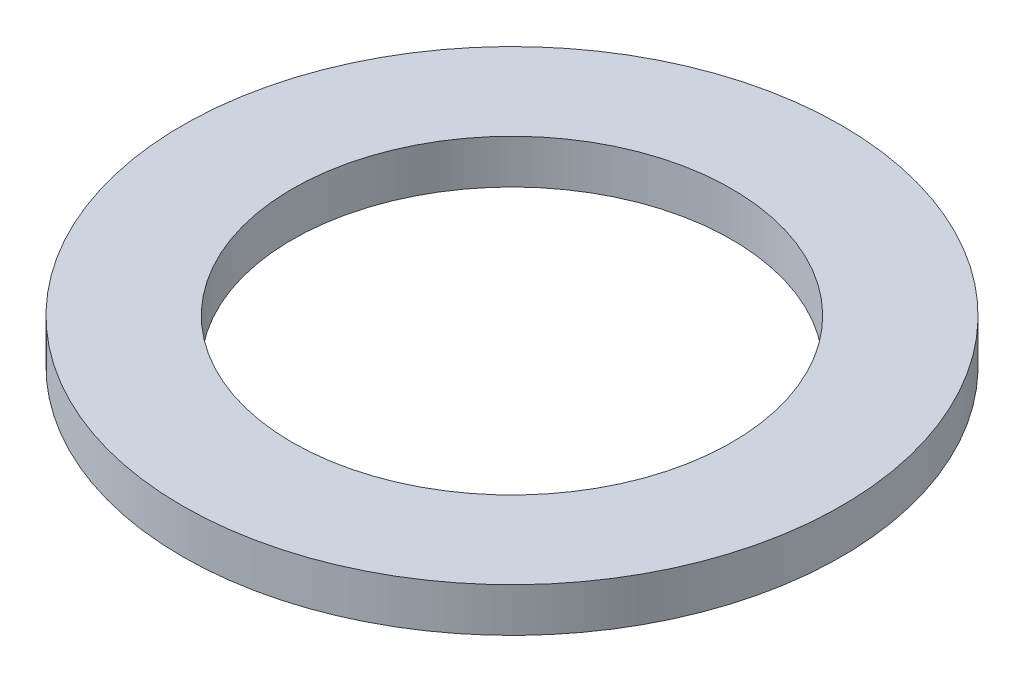
SolidWorks part; units mm, degrees
ref_plane "Front Plane" through (0, 0, 0) normal (0, 0, 1) x (1, 0, 0)
ref_plane "Top Plane" through (0, 0, 0) normal (0, 1, 0) x (1, 0, 0)
ref_plane "Right Plane" through (0, 0, 0) normal (1, 0, 0) x (0, 0, -1)
sketch "Sketch1" plane through (0, 0, 0) normal (0, 1, 0) x (1, 0, 0)
  circle A0 centre (0, 0) radius 10
  circle A1 centre (0, 0) radius 15
  dimension "D1" = 30
  dimension "D2" = 20
extrude "Boss-Extrude1" add sketch "Sketch1" along normal blind 2
